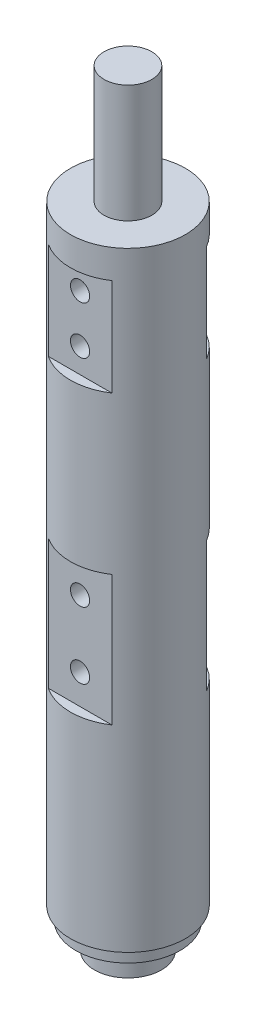
SolidWorks part; units mm, degrees
ref_plane "Front Plane" through (0, 0, 0) normal (0, 0, 1) x (1, 0, 0)
ref_plane "Top Plane" through (0, 0, 0) normal (0, 1, 0) x (1, 0, 0)
ref_plane "Right Plane" through (0, 0, 0) normal (1, 0, 0) x (0, 0, -1)
sketch "Sketch1" plane through (0, 0, 0) normal (0, 1, 0) x (1, 0, 0)
  circle A0 centre (0, 0) radius 19.05
  dimension "D1" = 38.1
extrude "Boss-Extrude1" add sketch "Sketch1" along normal blind 254
sketch "Sketch2" plane through (0, 0, 0) normal (0, 0, 1) x (1, 0, 0)
  line L0 (19.05, 0) -> (11.1125, 0)
  line L1 (11.1125, 0) -> (11.1125, 8.636)
  line L2 (11.1125, 8.636) -> (17.272, 8.636)
  line L3 (17.272, 8.636) -> (17.272, 12.954)
  line L4 (17.272, 12.954) -> (19.05, 12.954)
  line L5 (19.05, 0) -> (19.05, 254) construction
  line L6 (19.05, 254) -> (19.05, 215.011)
  line L7 (19.05, 254) -> (-19.05, 254) construction
  line L8 (19.05, 254) -> (-19.05, 254) construction
  line L9 (19.05, 215.011) -> (7.9375, 215.011)
  line L10 (7.9375, 215.011) -> (7.9375, 254)
  line L11 (7.9375, 254) -> (19.05, 254)
  line L12 (19.05, 0) -> (19.05, 12.954)
  line L13 (0, 348.3373) -> (0, -79.5423) construction
  dimension "D1" = 11.1125
  dimension "D2" = 17.272
  dimension "D3" = 8.636
  dimension "D4" = 4.318
  dimension "D5" = 7.9375
  dimension "D8" = 206.375
revolve "Cut-Revolve1" cut sketch "Sketch2" angle 360 about L13
sketch "Sketch3" plane through (0, 0, 0) normal (1, 0, 0) x (0, 0, -1)
  line L0 (0, 334.7642) -> (0, -20.7307) construction
  line L1 (19.05, 12.954) -> (19.05, 215.011) construction
  line L2 (19.05, 205.486) -> (9.525, 205.486)
  line L3 (19.05, 205.486) -> (19.05, 173.228)
  line L4 (19.05, 173.228) -> (9.525, 173.228)
  line L5 (9.525, 205.486) -> (9.525, 173.228)
  line L6 (19.05, 12.954) -> (19.05, 215.011) construction
  line L7 (19.05, 121.158) -> (9.525, 121.158)
  line L8 (19.05, 121.158) -> (19.05, 77.978)
  line L9 (19.05, 77.978) -> (9.525, 77.978)
  line L10 (9.525, 121.158) -> (9.525, 77.978)
  line L11 (62.8261, 109.982) -> (-27.1107, 109.982) construction
  line L12 (56.0678, 189.357) -> (-35.4285, 189.357) construction
  line L13 (19.05, 215.011) -> (-19.05, 215.011) construction
  line L14 (-19.05, 205.486) -> (-19.05, 173.228)
  line L15 (-19.05, 121.158) -> (-19.05, 77.978)
  line L16 (-19.05, 205.486) -> (-15.875, 205.486)
  line L17 (-15.875, 205.486) -> (-15.875, 173.228)
  line L18 (-15.875, 173.228) -> (-19.05, 173.228)
  line L19 (-19.05, 121.158) -> (-15.875, 121.158)
  line L20 (-15.875, 121.158) -> (-15.875, 77.978)
  line L21 (-15.875, 77.978) -> (-19.05, 77.978)
  dimension "D1" = 43.18
  dimension "D2" = 32.258
  dimension "D3" = 11.176
  dimension "D4" = 79.375
  dimension "D5" = 9.525
  dimension "D6" = 9.525
  dimension "D7" = 3.175
extrude "Cut-Extrude1" cut sketch "Sketch3" against normal through all and the other way through all
hole_wizard "1 (1) Diameter Hole1" positions "Sketch5" profile "Sketch6" hole size "1" standard "ANSI Inch" end condition through all
sketch "Sketch5" plane through (0, 0, -9.525) normal (0, 0, -1) x (-1, 0, 0)
  line L0 (0, 325.237) -> (0, -21.1805) construction
  line L1 (-16.4978, 121.158) -> (16.4978, 121.158) construction
  line L3 (-16.4978, 173.228) -> (-16.4978, 205.486) construction
  line L4 (-16.4978, 173.228) -> (-16.4978, 205.486) construction
  line L5 (-16.4978, 189.357) -> (10.79, 189.357) construction
  point P18 (0, 197.2945)
  point P20 (0, 181.4195)
  point P22 (0, 109.982)
  point P24 (0, 87.884)
  dimension "D1" = 11.176
  dimension "D2" = 22.098
  dimension "D3" = 15.875
sketch "Sketch6" plane through (0, 197.2945, -9.525) normal (1, 0, 0) x (0, 1, 0)
  line L0 (0, 0) -> (0, 28.575)
  line L1 (0, 28.575) -> (3.175, 28.575)
  line L2 (3.175, 28.575) -> (3.175, 0)
  line L5 (3.175, 0) -> (0, 0)
  line L11 (0, -6.35) -> (0, 107.95) construction
  dimension "Thru Hole Dia." = 6.35
  dimension "Thru Hole Depth" = 28.575
